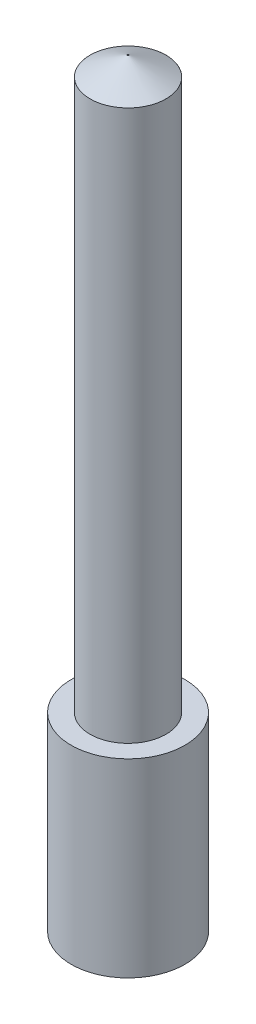
SolidWorks part; units mm, degrees
ref_plane "Płaszczyzna przednia" through (0, 0, 0) normal (0, 0, 1) x (1, 0, 0)
ref_plane "Płaszczyzna górna" through (0, 0, 0) normal (0, 1, 0) x (1, 0, 0)
ref_plane "Płaszczyzna prawa" through (0, 0, 0) normal (1, 0, 0) x (0, 0, -1)
sketch "Szkic1" plane through (0, 0, 0) normal (0, 1, 0) x (1, 0, 0)
  circle A0 centre (0, 0) radius 10
  dimension "D1" = 20
extrude "Dodanie-wyciągnięcie1" add sketch "Szkic1" along normal blind 195
sketch "Szkic2" plane through (0, 195, 0) normal (0, 1, 0) x (1, 0, 0)
  circle A0 centre (0, 0) radius 10
extrude "Dodanie-wyciągnięcie2" add sketch "Szkic2" along normal blind 5 draft 63 separate body
sketch "Szkic3" plane through (0, 0, 0) normal (0, -1, 0) x (1, 0, 0)
  circle A0 centre (0, 0) radius 15
extrude "Dodanie-wyciągnięcie3" add sketch "Szkic3" against normal blind 50
